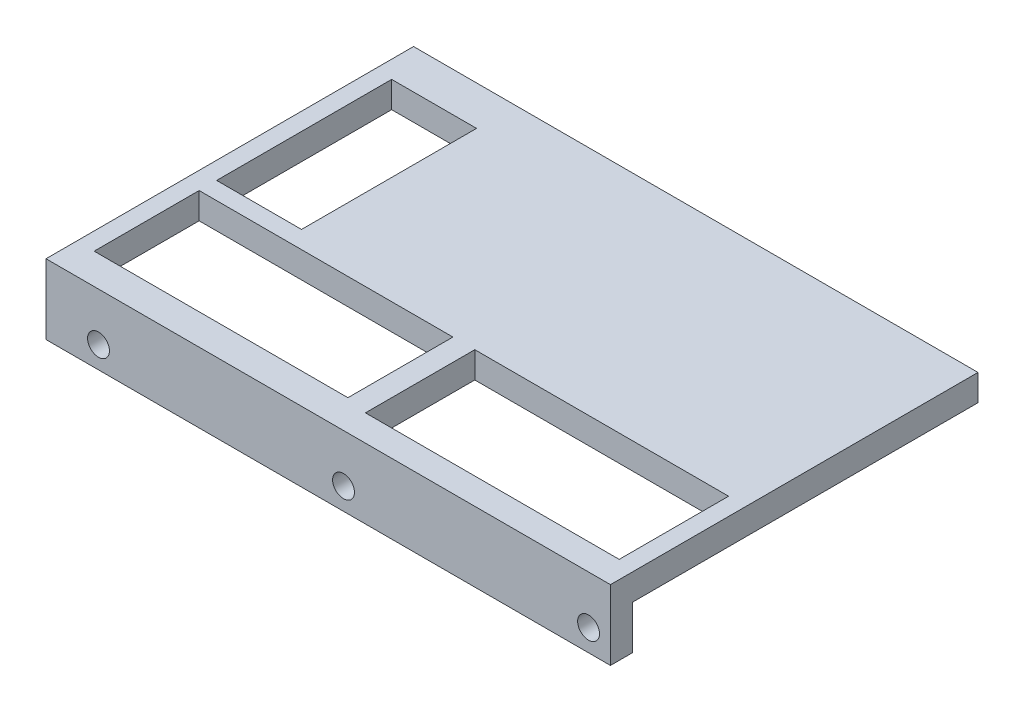
SolidWorks part; units mm, degrees
ref_plane "Front Plane" through (0, 0, 0) normal (0, 0, 1) x (1, 0, 0)
ref_plane "Top Plane" through (0, 0, 0) normal (0, 1, 0) x (1, 0, 0)
ref_plane "Right Plane" through (0, 0, 0) normal (1, 0, 0) x (0, 0, -1)
sketch "Sketch1" plane through (0, 0, 0) normal (0, 1, 0) x (1, 0, 0)
  line L1 (0, 0) -> (64.5, 0)
  line L2 (0, 0) -> (0, 42)
  line L3 (0, 42) -> (64.5, 42)
  line L4 (64.5, 0) -> (64.5, 42)
  dimension "D1" = 64.5
  dimension "D2" = 42
extrude "Boss-Extrude1" add sketch "Sketch1" along normal blind 3
sketch "Sketch2" plane through (0, 3, 0) normal (0, 1, 0) x (1, 0, 0)
  line L21 (0, 0) -> (64.5, 0) construction
  line L22 (62.5, 3) -> (33.5, 3)
  line L23 (62.5, 3) -> (62.5, 15.5)
  line L24 (62.5, 15.5) -> (33.5, 15.5)
  line L25 (33.5, 3) -> (33.5, 15.5)
  line L26 (31, 3.5) -> (2, 3.5)
  line L27 (31, 3.5) -> (31, 15.5)
  line L28 (31, 15.5) -> (2, 15.5)
  line L29 (2, 3.5) -> (2, 15.5)
  line L30 (11.7, 17.5) -> (2, 17.5)
  line L31 (11.7, 17.5) -> (11.7, 37.5)
  line L32 (11.7, 37.5) -> (2, 37.5)
  line L33 (2, 17.5) -> (2, 37.5)
  line L34 (64.5, 0) -> (64.5, 42) construction
  line L35 (0, 42) -> (0, 0) construction
  dimension "D1" = 12
  dimension "D2" = 12.5
  dimension "D3" = 3.5
  dimension "D4" = 29
  dimension "D5" = 29
  dimension "D6" = 20
  dimension "D7" = 9.7
  dimension "D8" = 2
  dimension "D9" = 2
  dimension "D10" = 2
  dimension "D11" = 0.5
extrude "Cut-Extrude1" cut sketch "Sketch2" against normal up to next
sketch "Sketch5" plane through (0, 0, 0) normal (0, -1, 0) x (1, 0, 0)
  line L1 (0, 0) -> (64.5, 0)
  line L2 (0, 0) -> (0, -2.5)
  line L3 (0, -2.5) -> (64.5, -2.5)
  line L4 (64.5, 0) -> (64.5, -2.5)
  line L7 (0, 0) -> (64.5, 0) construction
  line L8 (64.5, 0) -> (64.5, -42) construction
  line L9 (0, -42) -> (0, 0) construction
  dimension "D1" = 2.5
extrude "Boss-Extrude4" add sketch "Sketch5" along normal blind 5
sketch "Sketch4" plane through (0, 0, 0) normal (0, 0, 1) x (1, 0, 0)
  line L4 (64.5, -5) -> (0, -5) construction
  circle A0 centre (62, -2.5) radius 1.25
  circle A1 centre (6, -2.5) radius 1.25
  circle A2 centre (34, -2.5) radius 1.25
  point P8 (0, 0)
  point P9 (0, 0)
  point P10 (0, 0)
  dimension "D1" = 2.5
  dimension "D4" = 2.5
  dimension "D2" = 56
  dimension "D3" = 2.5
  dimension "D5" = 28
extrude "Cut-Extrude2" cut sketch "Sketch4" against normal up to next
